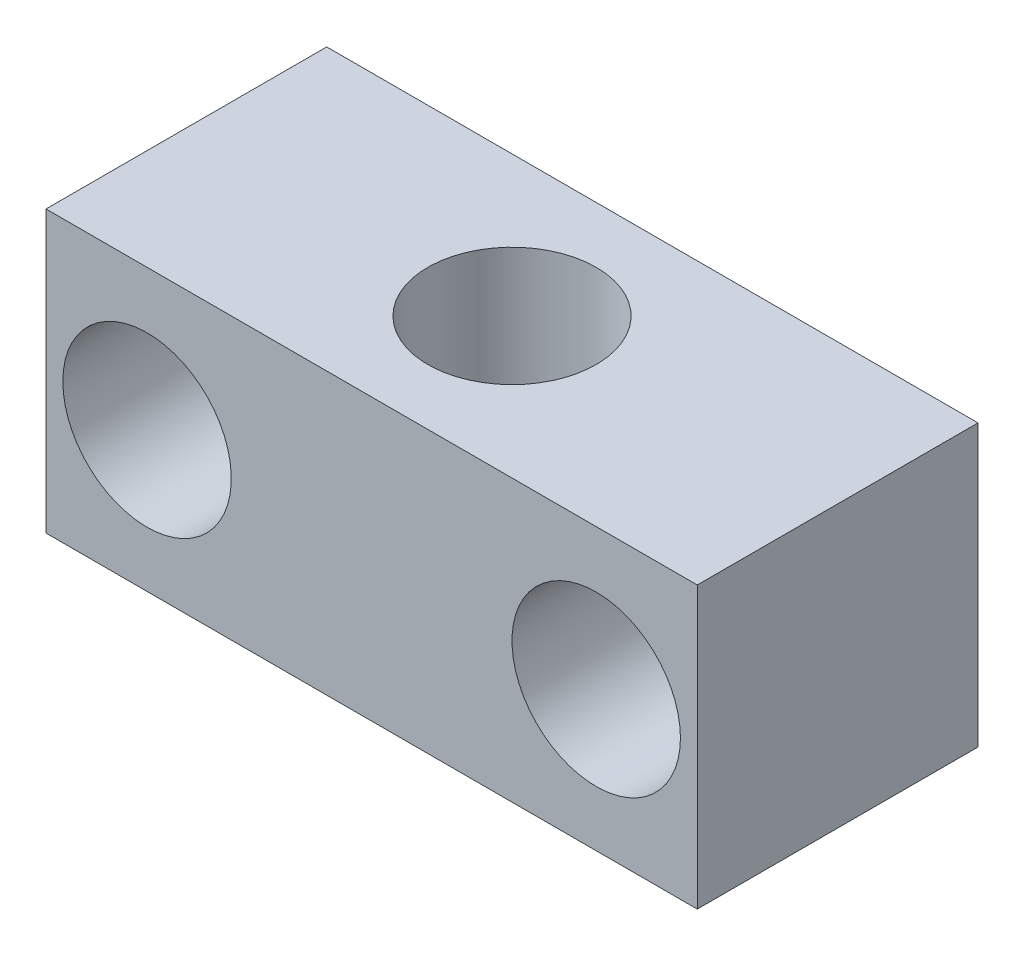
SolidWorks part; units mm, degrees
ref_plane "Front Plane" through (0, 0, 0) normal (0, 0, 1) x (1, 0, 0)
ref_plane "Top Plane" through (0, 0, 0) normal (0, 1, 0) x (1, 0, 0)
ref_plane "Right Plane" through (0, 0, 0) normal (1, 0, 0) x (0, 0, -1)
sketch "Sketch1" plane through (0, 0, 0) normal (0, 0, 1) x (1, 0, 0)
  line L1 (-12.4697, 1.525) -> (-0.4697, 1.525)
  line L2 (-12.4697, 1.525) -> (-12.4697, -3.475)
  line L3 (-12.4697, -3.475) -> (-0.4697, -3.475)
  line L4 (-0.4697, 1.525) -> (-0.4697, -3.475)
  dimension "D1" = 12
  dimension "D2" = 5
extrude "Boss-Extrude1" add sketch "Sketch1" along normal blind 5
sketch "Sketch2" plane through (0, -3.475, 0) normal (0, -1, 0) x (1, 0, 0)
  line L0 (-12.4697, 5) -> (-12.4697, 0) construction
  line L1 (-12.4697, 5) -> (-0.4697, 5) construction
  circle A0 centre (-6.4697, 2.5) radius 1.5
  point P2 (0, 0)
  point P5 (-12.4697, 2.5)
  point P6 (0, 0)
  point P9 (-6.4697, 5)
  dimension "D1" = 3
extrude "Cut-Extrude1" cut sketch "Sketch2" against normal through all
sketch "Sketch3" plane through (0, 0, 0) normal (0, 0, -1) x (-1, 0, 0)
  line L0 (6.4697, -3.475) -> (6.4697, 1.525) construction
  line L1 (12.4697, -3.475) -> (0.4697, -3.475) construction
  line L2 (0.4697, 1.525) -> (12.4697, 1.525) construction
  line L3 (12.4697, 1.525) -> (12.4697, -3.475) construction
  circle A0 centre (10.4697, -0.9844) radius 1.5
  circle A1 centre (2.4697, -0.9844) radius 1.5
  dimension "D1" = 3
  dimension "D2" = 2
extrude "Cut-Extrude2" cut sketch "Sketch3" against normal through all
other "Move Face1" face at (-0.4697, -0.975, 2.5) face at (-12.4697, -0.975, 2.5) parameters "D1"=0.2
